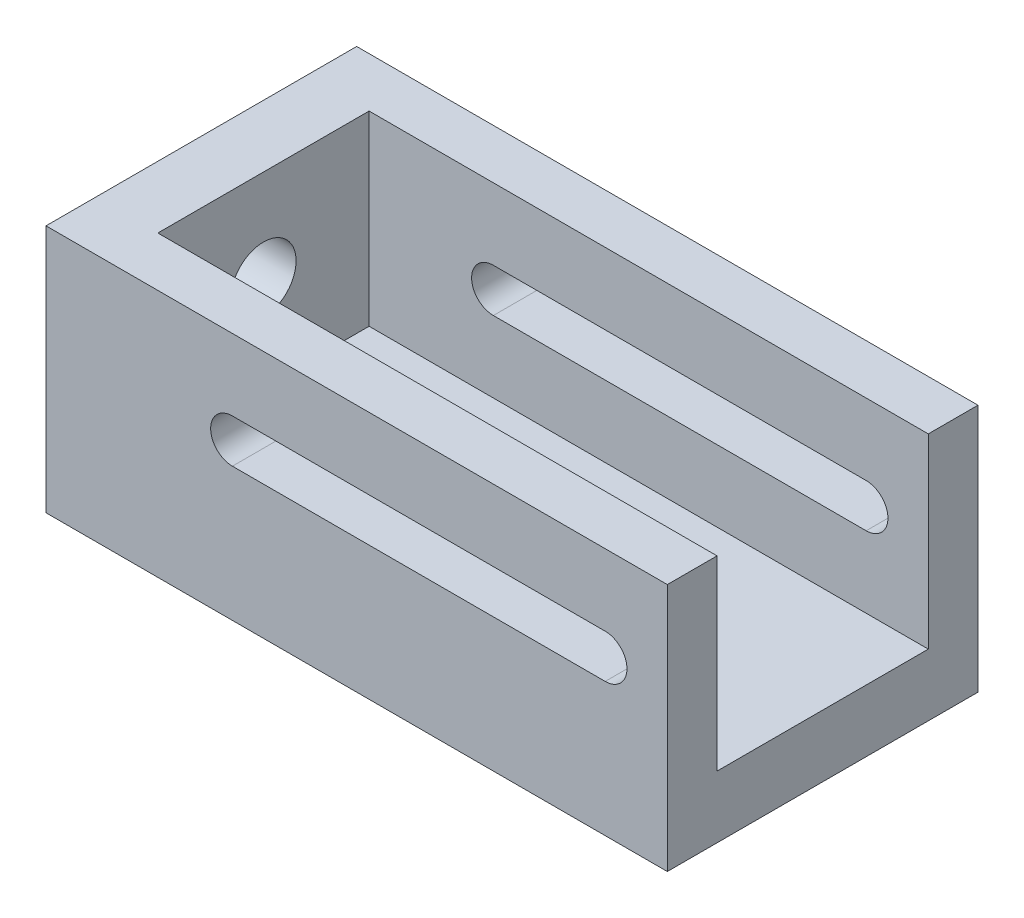
SolidWorks part; units mm, degrees
ref_plane "Plan de face" through (0, 0, 0) normal (0, 0, 1) x (1, 0, 0)
ref_plane "Plan de dessus" through (0, 0, 0) normal (0, 1, 0) x (1, 0, 0)
ref_plane "Plan de droite" through (0, 0, 0) normal (1, 0, 0) x (0, 0, -1)
sketch "Esquisse1" plane through (0, 0, 0) normal (0, 1, 0) x (1, 0, 0)
  line L1 (-50, -25) -> (50, -25)
  line L2 (-50, -25) -> (-50, 25)
  line L3 (-50, 25) -> (50, 25)
  line L4 (50, -25) -> (50, 25)
  line L5 (-50, -25) -> (50, 25) construction
  line L6 (-50, 25) -> (50, -25) construction
  point P0 (0, 0)
  dimension "D1" = 100
  dimension "D2" = 50
extrude "Boss.-Extru.1" add sketch "Esquisse1" along normal blind 10
sketch "Esquisse2" plane through (0, 10, 0) normal (0, 1, 0) x (1, 0, 0)
  line L0 (50, -25) -> (50, 25) construction
  line L1 (-50, -25) -> (50, -25)
  line L2 (-50, -25) -> (-50, -17)
  line L3 (-50, -17) -> (50, -17)
  line L4 (50, -25) -> (50, -17)
  line L6 (-50, 25) -> (50, 25)
  line L7 (-50, 25) -> (-50, 17)
  line L8 (-50, 17) -> (50, 17)
  line L9 (50, 25) -> (50, 17)
  dimension "D1" = 8
  dimension "D2" = 8
extrude "Boss.-Extru.2" add sketch "Esquisse2" along normal blind 30
sketch "Esquisse3" plane through (0, 10, 0) normal (0, 1, 0) x (1, 0, 0)
  line L0 (50, -17) -> (-50, -17) construction
  line L1 (-50, 17) -> (-40, 17)
  line L2 (-50, 17) -> (-50, -17)
  line L3 (-50, -17) -> (-40, -17)
  line L4 (-40, 17) -> (-40, -17)
  dimension "D1" = 10
extrude "Boss.-Extru.3" add sketch "Esquisse3" along normal blind 30
sketch "Esquisse5" plane through (-50, 0, 0) normal (-1, 0, 0) x (0, 0, 1)
  line L0 (-25, 40) -> (25, 40) construction
  circle A0 centre (0, 25) radius 5.25
  dimension "D1" = 10.5
  dimension "D2" = 15
extrude "Enlèv. mat.-Extru.1" cut sketch "Esquisse5" against normal through all
sketch "Esquisse8" plane through (0, 0, 25) normal (0, 0, 1) x (1, 0, 0)
  line L0 (-20, 25) -> (40, 25) construction
  line L1 (-20, 28.5) -> (40, 28.5)
  line L2 (-20, 21.5) -> (40, 21.5)
  line L3 (-50, 40) -> (50, 40) construction
  line L4 (50, 40) -> (50, 0) construction
  arc A0 (-20, 28.5) -> (-20, 21.5) centre (-20, 25) ccw
  arc A1 (40, 21.5) -> (40, 28.5) centre (40, 25) ccw
  point P2 (10, 25)
  dimension "D1" = 3.5
  dimension "D2" = 60
  dimension "D3" = 15
  dimension "D4" = 10
extrude "Enlèv. mat.-Extru.4" cut sketch "Esquisse8" against normal through all
hole_wizard "Chambrage pour vis à tête ronde bombée M51" positions "Esquisse9" profile "Esquisse10" counterbore size "M5" standard "Ansi Metric" end condition through all
sketch "Esquisse9" plane through (0, 10, 0) normal (0, 1, 0) x (1, 0, 0)
  line L2 (-40, -17) -> (-40, 17) construction
  point P0 (-25, 0)
  point P2 (0, 0)
  dimension "D1" = 25
  dimension "D2" = 15
sketch "Esquisse10" plane through (-25, 10, 0) normal (1, 0, 0) x (0, 0, 1)
  line L0 (0, 0) -> (0, 10)
  line L1 (0, 10) -> (2.75, 10)
  line L3 (2.75, 10) -> (2.75, 5)
  line L4 (2.75, 5) -> (5, 5)
  line L5 (5, 5) -> (5, 0)
  line L7 (5, 0) -> (0, 0)
  line L11 (0, -6.35) -> (0, 107.95) construction
  dimension "Diamètre du perçage jusqu'au prochain" = 5.5
  dimension "Profondeur du perçage jusqu'au prochain" = 10
  dimension "Diamètre du chambrage" = 10
  dimension "Profondeur du chambrage" = 5
